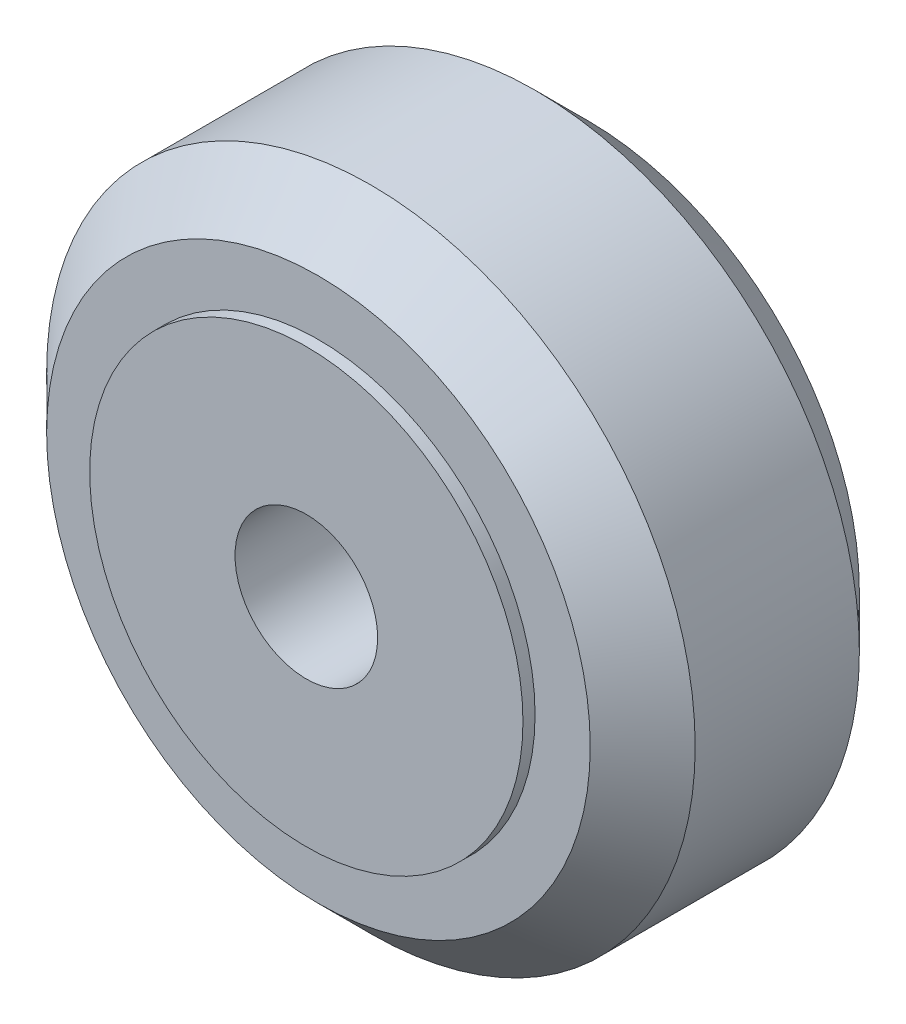
SolidWorks part; units mm, degrees
ref_plane "Front Plane" through (0, 0, 0) normal (0, 0, 1) x (1, 0, 0)
ref_plane "Top Plane" through (0, 0, 0) normal (0, 1, 0) x (1, 0, 0)
ref_plane "Right Plane" through (0, 0, 0) normal (1, 0, 0) x (0, 0, -1)
sketch "Sketch2" plane through (0, 0, 0) normal (1, 0, 0) x (0, 0, -1)
  line L0 (-5.45, 2.65) -> (5.45, 2.65)
  line L2 (5, 10.1) -> (3.05, 12.05)
  line L3 (3.05, 12.05) -> (-3.05, 12.05)
  line L4 (-3.05, 12.05) -> (-5, 10.1)
  line L6 (5.45, 2.65) -> (5.45, 8.05)
  line L7 (5.45, 8.05) -> (5, 8.05)
  line L8 (5, 8.05) -> (5, 10.1)
  line L9 (-5.45, 2.65) -> (-5.45, 8.05)
  line L10 (-5.45, 8.05) -> (-5, 8.05)
  line L11 (-5, 8.05) -> (-5, 10.1)
  line L12 (-10.4458, 0) -> (13.9089, 0) construction
  point P3 (0, 2.65)
  point P7 (0, 12.05)
  dimension "D1" = 10.9
  dimension "D2" = 10
  dimension "D3" = 5.3
  dimension "D4" = 16.1
  dimension "D5" = 24.1
  dimension "D6" = 6.1
revolve "Revolve1" add sketch "Sketch2" angle 360 about L12
